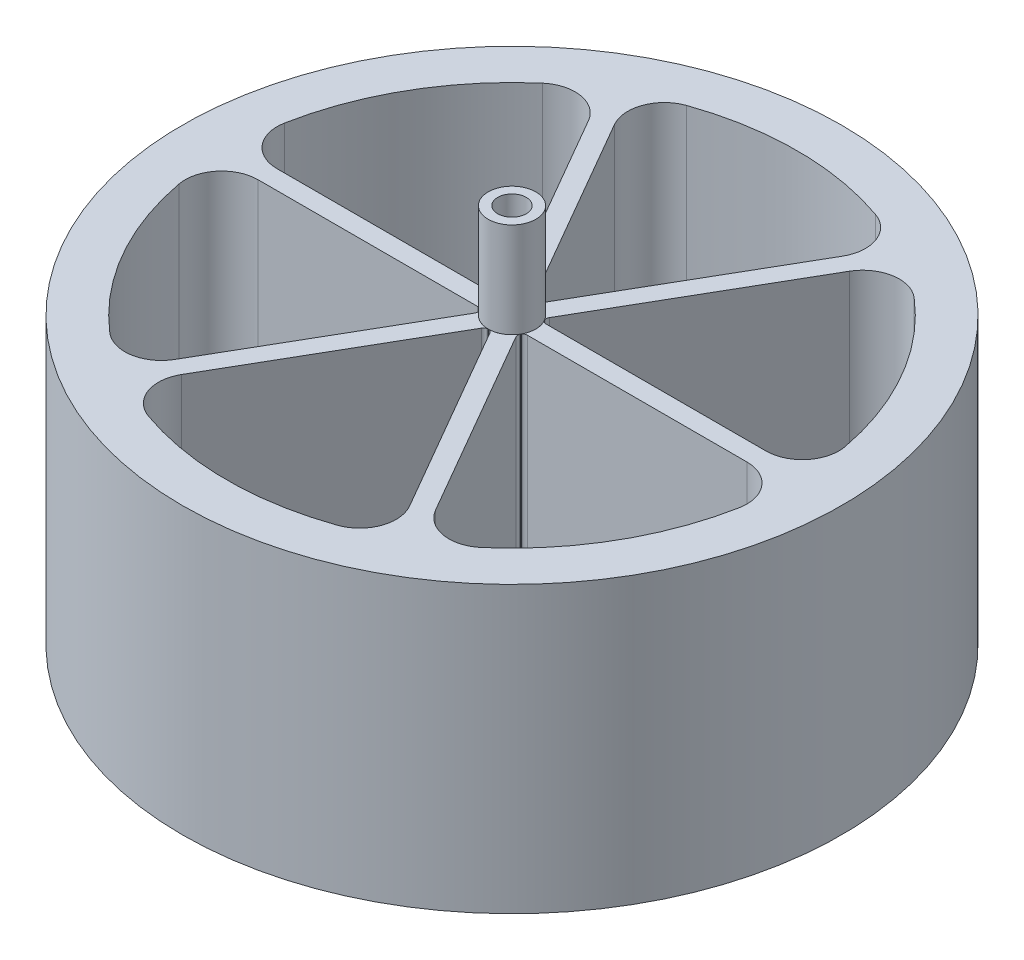
SolidWorks part; units mm, degrees
ref_plane "Front Plane" through (0, 0, 0) normal (0, 0, 1) x (1, 0, 0)
ref_plane "Top Plane" through (0, 0, 0) normal (0, 1, 0) x (1, 0, 0)
ref_plane "Right Plane" through (0, 0, 0) normal (1, 0, 0) x (0, 0, -1)
sketch "Sketch1" plane through (0, 0, 0) normal (0, 1, 0) x (1, 0, 0)
  circle A0 centre (0, 0) radius 1.5
  circle A1 centre (0, 0) radius 2.5
  dimension "D1" = 3
  dimension "D2" = 5
extrude "Boss-Extrude1" add sketch "Sketch1" along normal blind 10
sketch "Sketch2" plane through (0, 0, 0) normal (0, -1, 0) x (-1, 0, 0)
  line L1 (2.614, 1) -> (25.708, 1)
  line L2 (20.4475, 0) -> (20.4475, 1)
  line L3 (2.614, -1) -> (25.708, -1)
  line L4 (0.4409, -2.7637) -> (11.988, -22.7638)
  line L5 (2.173, -1.7637) -> (13.72, -21.7638)
  line L6 (-2.173, -1.7637) -> (-13.72, -21.7638)
  line L7 (-0.4409, -2.7637) -> (-11.988, -22.7638)
  line L8 (-2.614, 1) -> (-25.708, 1)
  line L9 (-2.614, -1) -> (-25.708, -1)
  line L10 (-0.4409, 2.7637) -> (-11.988, 22.7638)
  line L11 (-2.173, 1.7637) -> (-13.72, 21.7638)
  line L12 (2.173, 1.7637) -> (13.72, 21.7638)
  line L13 (0.4409, 2.7637) -> (11.988, 22.7638)
  line L14 (0.0941, -2.5116) -> (0.0272, -2.4999)
  line L15 (-0.0941, -2.5116) -> (-0.052, -2.4995)
  line L16 (2.2222, -1.1743) -> (2.1785, -1.2264)
  line L17 (2.128, -1.3373) -> (2.1386, -1.2947)
  line L18 (2.128, 1.3373) -> (2.1514, 1.2734)
  line L19 (2.2222, 1.1743) -> (2.1906, 1.2047)
  line L20 (-0.0941, 2.5116) -> (-0.0272, 2.4999)
  line L21 (0.0941, 2.5116) -> (0.052, 2.4995)
  line L22 (-2.2222, 1.1743) -> (-2.1785, 1.2264)
  line L23 (-2.128, 1.3373) -> (-2.1386, 1.2947)
  line L24 (-2.128, -1.3373) -> (-2.1514, -1.2734)
  line L25 (-2.2222, -1.1743) -> (-2.1906, -1.2047)
  arc A0 (9.9338, -28.3076) -> (19.5482, -22.7567) centre (0, 0) ccw
  arc A1 (25.708, 1) -> (29.482, 5.5509) centre (25.708, 4.8403) ccw
  circle A2 centre (0, 0) radius 2.5 construction
  arc A3 (2.2222, 1.1743) -> (2.614, 1) centre (2.614, 1.5276) ccw
  arc A4 (0.0272, -2.4999) -> (2.1386, -1.2947) centre (0, 0) ccw
  arc A5 (2.2222, -1.1743) -> (2.614, -1) centre (2.614, -1.5276) cw
  arc A6 (25.708, -1) -> (29.482, -5.5509) centre (25.708, -4.8403) cw
  arc A7 (2.128, -1.3373) -> (2.173, -1.7637) centre (2.6299, -1.5) ccw
  arc A8 (0.0941, -2.5116) -> (0.4409, -2.7637) centre (-0.0159, -3.0275) cw
  arc A9 (11.988, -22.7638) -> (9.9338, -28.3076) centre (8.6621, -24.6839) cw
  arc A10 (13.72, -21.7638) -> (19.5482, -22.7567) centre (17.0458, -19.8436) ccw
  arc A11 (-0.0941, -2.5116) -> (-0.4409, -2.7637) centre (0.0159, -3.0275) ccw
  arc A12 (-2.128, -1.3373) -> (-2.173, -1.7637) centre (-2.6299, -1.5) cw
  arc A13 (-13.72, -21.7638) -> (-19.5482, -22.7567) centre (-17.0458, -19.8436) cw
  arc A14 (-11.988, -22.7638) -> (-9.9338, -28.3076) centre (-8.6621, -24.6839) ccw
  arc A15 (-2.2222, -1.1743) -> (-2.614, -1) centre (-2.614, -1.5276) ccw
  arc A16 (-2.2222, 1.1743) -> (-2.614, 1) centre (-2.614, 1.5276) cw
  arc A17 (-25.708, 1) -> (-29.482, 5.5509) centre (-25.708, 4.8403) cw
  arc A18 (-25.708, -1) -> (-29.482, -5.5509) centre (-25.708, -4.8403) ccw
  arc A19 (-2.128, 1.3373) -> (-2.173, 1.7637) centre (-2.6299, 1.5) ccw
  arc A20 (-0.0941, 2.5116) -> (-0.4409, 2.7637) centre (0.0159, 3.0275) cw
  arc A21 (-11.988, 22.7638) -> (-9.9338, 28.3076) centre (-8.6621, 24.6839) cw
  arc A22 (-13.72, 21.7638) -> (-19.5482, 22.7567) centre (-17.0458, 19.8436) ccw
  arc A23 (0.0941, 2.5116) -> (0.4409, 2.7637) centre (-0.0159, 3.0275) ccw
  arc A24 (2.128, 1.3373) -> (2.173, 1.7637) centre (2.6299, 1.5) cw
  arc A25 (13.72, 21.7638) -> (19.5482, 22.7567) centre (17.0458, 19.8436) cw
  arc A26 (11.988, 22.7638) -> (9.9338, 28.3076) centre (8.6621, 24.6839) ccw
  arc A27 (-19.5482, -22.7567) -> (-9.9338, -28.3076) centre (0, 0) ccw
  arc A28 (-29.482, 5.5509) -> (-29.482, -5.5509) centre (0, 0) ccw
  arc A29 (-9.9338, 28.3076) -> (-19.5482, 22.7567) centre (0, 0) ccw
  arc A30 (19.5482, 22.7567) -> (9.9338, 28.3076) centre (0, 0) ccw
  arc A31 (29.482, -5.5509) -> (29.482, 5.5509) centre (0, 0) ccw
  arc A32 (-2.1514, -1.2734) -> (-0.052, -2.4995) centre (0, 0) ccw
  arc A33 (-2.1785, 1.2264) -> (-2.1906, -1.2047) centre (0, 0) ccw
  arc A34 (-0.0272, 2.4999) -> (-2.1386, 1.2947) centre (0, 0) ccw
  arc A35 (2.1514, 1.2734) -> (0.052, 2.4995) centre (0, 0) ccw
  arc A36 (2.1785, -1.2264) -> (2.1906, 1.2047) centre (0, 0) ccw
  point P85 (0, 0)
  point P108 (0, 0)
  dimension "D1" = 60
  dimension "D4" = 6
extrude "Boss-Extrude3" add sketch "Sketch2" along normal blind 30 separate body contours L6 A13 A27 A14 L7 A11 L15 A32 L24 A12 | L4 A9 A0 A10 L5 A7 L17 A4 L14 A8 | L1 A1 A31 A6 L3 A5 L16 A36 L19 A3 | L13 A26 A30 A25 L12 A24 L18 A35 L21 A23 | L11 A22 A29 A21 L10 A20 L20 A34 L23 A19 | L9 A18 A28 A17 L8 A16 L22 A33 L25 A15
sketch "Sketch5" plane through (0, -30, 0) normal (0, -1, 0) x (-1, 0, 0)
  circle A0 centre (0, 0) radius 30
  circle A1 centre (0, 0) radius 34.6666
extrude "Boss-Extrude4" add sketch "Sketch5" against normal blind 30
sketch "Sketch6" plane through (0, 10, 0) normal (0, 1, 0) x (1, 0, 0)
  circle A0 centre (0, 0) radius 1.5
extrude "Boss-Extrude5" add sketch "Sketch6" against normal blind 10
sketch "Sketch7" plane through (0, 10, 0) normal (0, 1, 0) x (1, 0, 0)
  circle A0 centre (0, 0) radius 1.5
  dimension "D1" = 3
extrude "Cut-Extrude1" cut sketch "Sketch7" against normal blind 9
